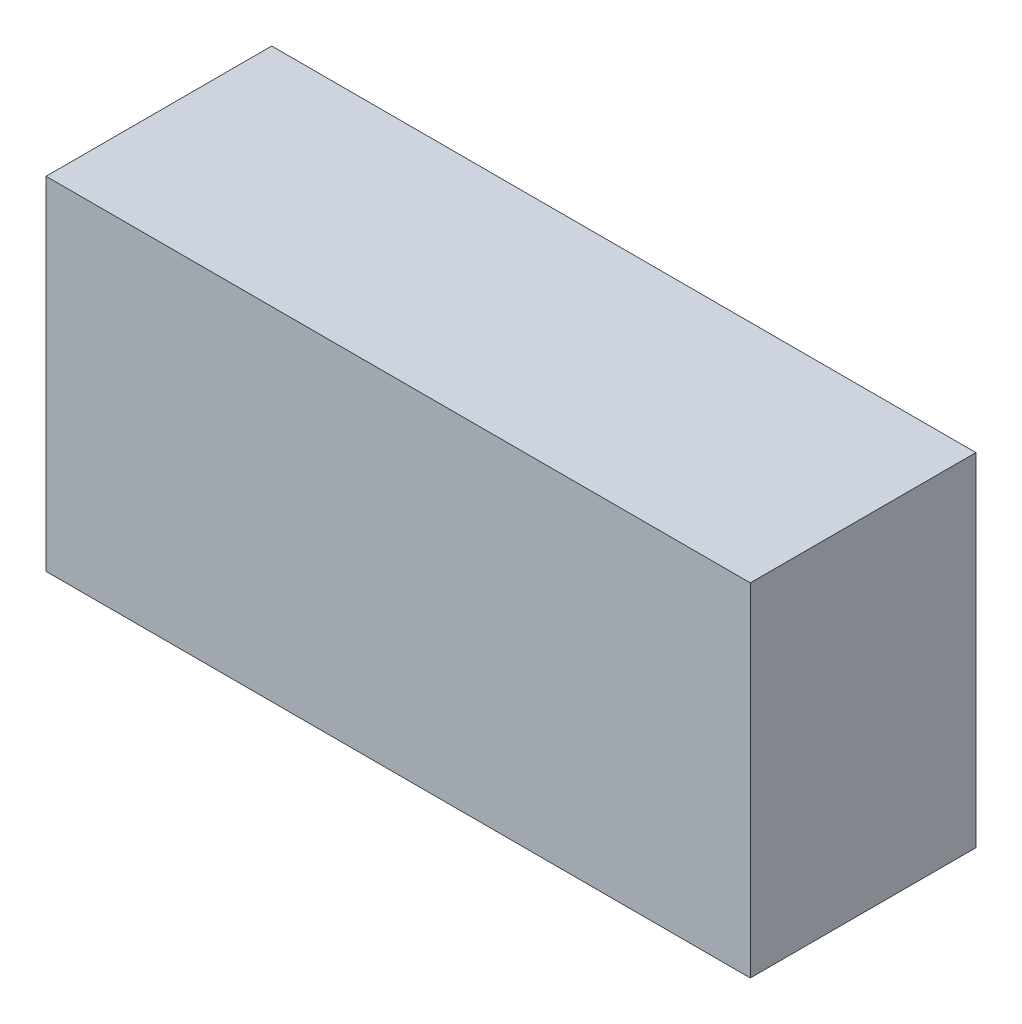
SolidWorks part; units mm, degrees
ref_plane "Front Plane" through (0, 0, 0) normal (0, 0, 1) x (1, 0, 0)
ref_plane "Top Plane" through (0, 0, 0) normal (0, 1, 0) x (1, 0, 0)
ref_plane "Right Plane" through (0, 0, 0) normal (1, 0, 0) x (0, 0, -1)
sketch "Sketch2" plane through (0, 0, 0) normal (0, 1, 0) x (1, 0, 0)
  line L1 (0, 0) -> (72.136, 0)
  line L2 (0, 0) -> (0, 23.114)
  line L3 (0, 23.114) -> (72.136, 23.114)
  line L4 (72.136, 0) -> (72.136, 23.114)
  dimension "D1" = 23.114
  dimension "D2" = 72.136
extrude "Boss-Extrude1" add sketch "Sketch2" along normal blind 35.052
